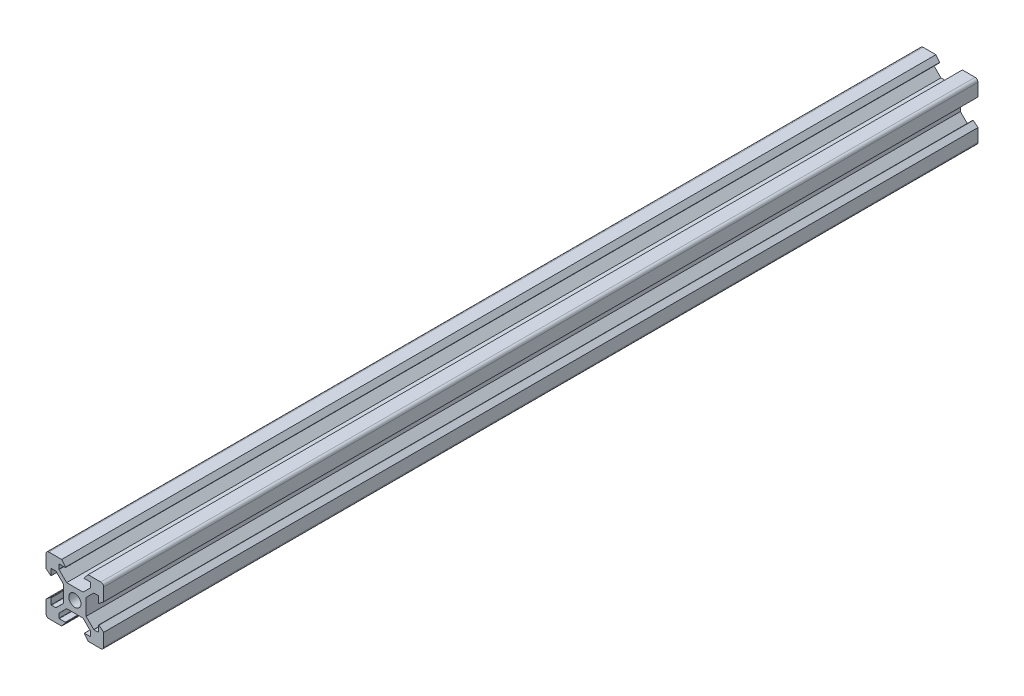
SolidWorks part; units mm, degrees
ref_plane "Front Plane" through (0, 0, 0) normal (0, 0, 1) x (1, 0, 0)
ref_plane "Top Plane" through (0, 0, 0) normal (0, 1, 0) x (1, 0, 0)
ref_plane "Right Plane" through (0, 0, 0) normal (1, 0, 0) x (0, 0, -1)
sketch "Sketch1" plane through (0, 0, 0) normal (0, 0, 1) x (1, 0, 0)
  line L0 (-2.8393, 3.9) -> (-5.4707, 6.5314)
  line L1 (-10, 10) -> (-4.58, 10)
  line L2 (-10, 10) -> (-10, 4.58)
  line L3 (-10, -10) -> (-4.58, -10)
  line L4 (10, 10) -> (10, 4.58)
  line L5 (-10, 10) -> (-3.9, 3.9) construction
  line L6 (-10, -10) -> (-4.061, -4.061) construction
  line L7 (-2.8393, 3.9) -> (2.8393, 3.9)
  line L8 (-3.9, 2.8393) -> (-3.9, -2.8393)
  line L9 (-2.8393, -3.9) -> (2.8393, -3.9)
  line L10 (3.9, 2.8393) -> (3.9, -2.8393)
  line L11 (-1.4849, 1.4849) -> (3.9, -3.9) construction
  line L12 (-3.9, -3.9) -> (1.4849, 1.4849) construction
  line L13 (-5.5, 6.6021) -> (-5.5, 8.1)
  line L14 (-5.4, 8.2) -> (-3.3344, 8.2)
  line L15 (-3.2566, 8.3629) -> (-4.58, 10)
  line L16 (0, 0) -> (0, 5.2663) construction
  line L17 (-3.9, 2.8393) -> (-6.5314, 5.4707)
  line L18 (-6.6021, 5.5) -> (-8.1, 5.5)
  line L19 (-8.2, 5.4) -> (-8.2, 3.3344)
  line L20 (-8.3629, 3.2566) -> (-10, 4.58)
  line L21 (8.3629, 3.2566) -> (10, 4.58)
  line L22 (8.2, 5.4) -> (8.2, 3.3344)
  line L23 (6.6021, 5.5) -> (8.1, 5.5)
  line L24 (3.9, 2.8393) -> (6.5314, 5.4707)
  line L25 (3.2566, 8.3629) -> (4.58, 10)
  line L26 (5.4, 8.2) -> (3.3344, 8.2)
  line L27 (2.8393, 3.9) -> (5.4707, 6.5314)
  line L28 (5.5, 6.6021) -> (5.5, 8.1)
  line L29 (55, 0) -> (-55, 0) construction
  line L30 (-8.3629, -3.2566) -> (-10, -4.58)
  line L31 (-8.2, -5.4) -> (-8.2, -3.3344)
  line L32 (-6.6021, -5.5) -> (-8.1, -5.5)
  line L33 (-3.9, -2.8393) -> (-6.5314, -5.4707)
  line L34 (-2.8393, -3.9) -> (-5.4707, -6.5314)
  line L35 (-5.5, -6.6021) -> (-5.5, -8.1)
  line L36 (-5.4, -8.2) -> (-3.3344, -8.2)
  line L37 (-3.2566, -8.3629) -> (-4.58, -10)
  line L38 (8.3629, -3.2566) -> (10, -4.58)
  line L39 (8.2, -5.4) -> (8.2, -3.3344)
  line L40 (6.6021, -5.5) -> (8.1, -5.5)
  line L41 (3.9, -2.8393) -> (6.5314, -5.4707)
  line L42 (2.8393, -3.9) -> (5.4707, -6.5314)
  line L43 (5.5, -6.6021) -> (5.5, -8.1)
  line L44 (5.4, -8.2) -> (3.3344, -8.2)
  line L45 (3.2566, -8.3629) -> (4.58, -10)
  line L46 (3.9, 3.9) -> (10, 10) construction
  line L47 (3.2459, -3.2459) -> (10, -10) construction
  line L48 (-10, -4.58) -> (-10, -10)
  line L49 (4.58, -10) -> (10, -10)
  line L50 (10, -4.58) -> (10, -10)
  line L51 (4.58, 10) -> (10, 10)
  circle A0 centre (0, 0) radius 2.1
  arc A1 (-5.4707, 6.5314) -> (-5.5, 6.6021) centre (-5.4, 6.6021) cw
  arc A2 (-5.5, 8.1) -> (-5.4, 8.2) centre (-5.4, 8.1) cw
  arc A3 (-3.3344, 8.2) -> (-3.2566, 8.3629) centre (-3.3344, 8.3) ccw
  arc A4 (-6.5314, 5.4707) -> (-6.6021, 5.5) centre (-6.6021, 5.4) ccw
  arc A5 (-8.1, 5.5) -> (-8.2, 5.4) centre (-8.1, 5.4) ccw
  arc A6 (-8.2, 3.3344) -> (-8.3629, 3.2566) centre (-8.3, 3.3344) cw
  arc A7 (8.2, 3.3344) -> (8.3629, 3.2566) centre (8.3, 3.3344) ccw
  arc A8 (8.1, 5.5) -> (8.2, 5.4) centre (8.1, 5.4) cw
  arc A9 (6.5314, 5.4707) -> (6.6021, 5.5) centre (6.6021, 5.4) cw
  arc A10 (3.3344, 8.2) -> (3.2566, 8.3629) centre (3.3344, 8.3) cw
  arc A11 (5.5, 8.1) -> (5.4, 8.2) centre (5.4, 8.1) ccw
  arc A12 (5.4707, 6.5314) -> (5.5, 6.6021) centre (5.4, 6.6021) ccw
  arc A13 (-8.2, -3.3344) -> (-8.3629, -3.2566) centre (-8.3, -3.3344) ccw
  arc A14 (-8.1, -5.5) -> (-8.2, -5.4) centre (-8.1, -5.4) cw
  arc A15 (-6.5314, -5.4707) -> (-6.6021, -5.5) centre (-6.6021, -5.4) cw
  arc A16 (-5.4707, -6.5314) -> (-5.5, -6.6021) centre (-5.4, -6.6021) ccw
  arc A17 (-5.5, -8.1) -> (-5.4, -8.2) centre (-5.4, -8.1) ccw
  arc A18 (-3.3344, -8.2) -> (-3.2566, -8.3629) centre (-3.3344, -8.3) cw
  arc A19 (8.2, -3.3344) -> (8.3629, -3.2566) centre (8.3, -3.3344) cw
  arc A20 (8.1, -5.5) -> (8.2, -5.4) centre (8.1, -5.4) ccw
  arc A21 (6.5314, -5.4707) -> (6.6021, -5.5) centre (6.6021, -5.4) ccw
  arc A22 (5.4707, -6.5314) -> (5.5, -6.6021) centre (5.4, -6.6021) cw
  arc A23 (5.5, -8.1) -> (5.4, -8.2) centre (5.4, -8.1) cw
  arc A24 (3.3344, -8.2) -> (3.2566, -8.3629) centre (3.3344, -8.3) ccw
  point P0 (0, 0)
  point P6 (0, 0)
  point P25 (-3.125, 8.2)
  dimension "D5" = 4.2
  dimension "D11" = 0.1
  dimension "D1" = 20
  dimension "D3" = 7.8
  dimension "D4" = 7.8
  dimension "D6" = 0.75
  dimension "D7" = 4.3
  dimension "D8" = 4.58
  dimension "D9" = 3.125
  dimension "D10" = 5.5
extrude "Boss-Extrude1" add sketch "Sketch1" along normal blind 303
fillet "Fillet1" radius 1 4 edges at (10, -10, 151.5) (10, 10, 151.5) (-10, -10, 151.5) (-10, 10, 151.5)
